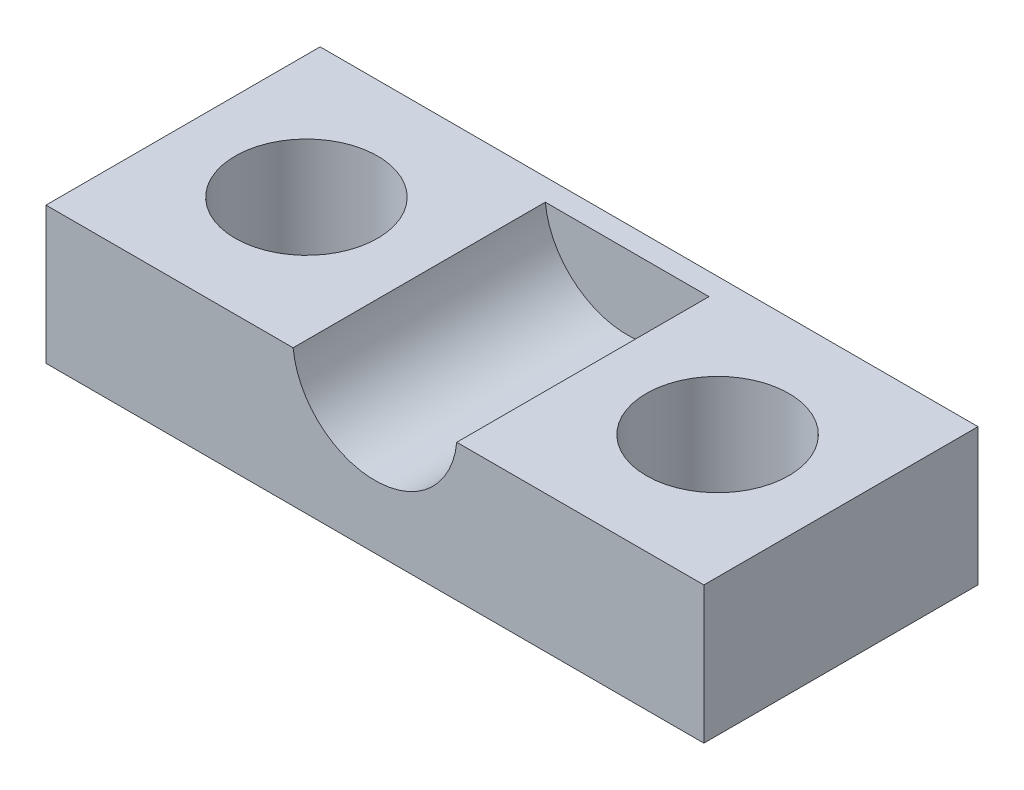
SolidWorks part; units mm, degrees
ref_plane "Front Plane" through (0, 0, 0) normal (0, 0, 1) x (1, 0, 0)
ref_plane "Top Plane" through (0, 0, 0) normal (0, 1, 0) x (1, 0, 0)
ref_plane "Right Plane" through (0, 0, 0) normal (1, 0, 0) x (0, 0, -1)
sketch "Sketch1" plane through (0, 0, 0) normal (0, 1, 0) x (1, 0, 0)
  line L1 (0, 0) -> (24, 0)
  line L2 (0, 0) -> (0, 10)
  line L3 (0, 10) -> (24, 10)
  line L4 (24, 0) -> (24, 10)
  circle A0 centre (4.5, 5) radius 2.6
  circle A1 centre (19.5, 5) radius 2.6
  dimension "D3" = 5.2
  dimension "D4" = 5.2
  dimension "D1" = 10
  dimension "D2" = 24
  dimension "D5" = 4.5
  dimension "D6" = 4.5
extrude "Boss-Extrude1" add sketch "Sketch1" along normal blind 5
sketch "Sketch2" plane through (0, 0, 0) normal (0, 0, 1) x (1, 0, 0)
  circle A0 centre (12, 5.3) radius 3
extrude "Cut-Extrude1" cut sketch "Sketch2" against normal blind 9.2
